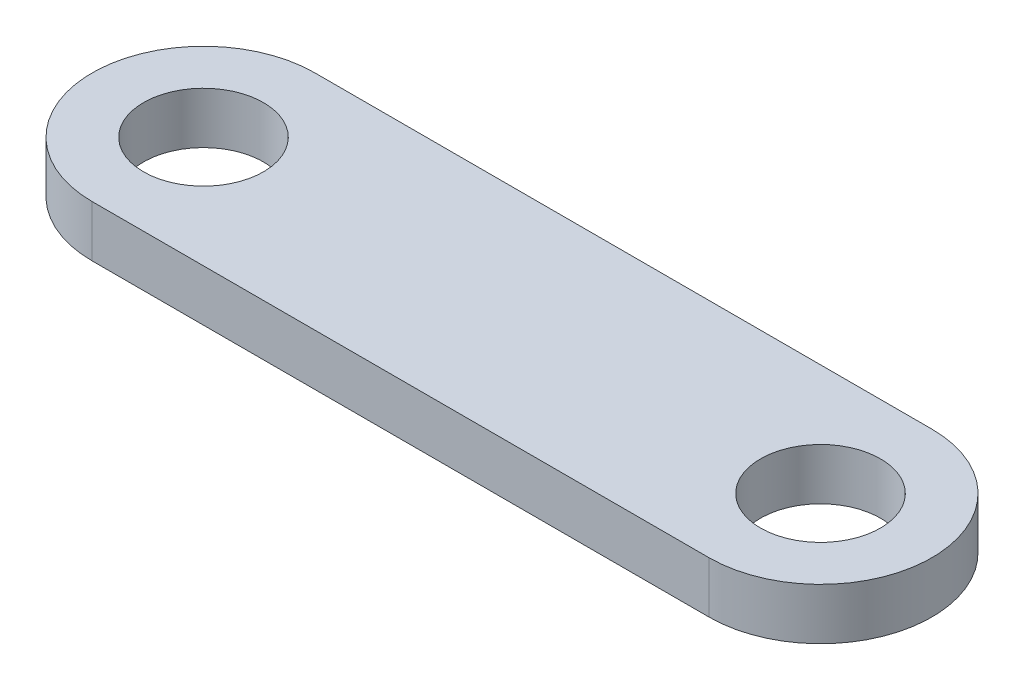
SolidWorks part; units mm, degrees
ref_plane "Front Plane" through (0, 0, 0) normal (0, 0, 1) x (1, 0, 0)
ref_plane "Top Plane" through (0, 0, 0) normal (0, 1, 0) x (1, 0, 0)
ref_plane "Right Plane" through (0, 0, 0) normal (1, 0, 0) x (0, 0, -1)
sketch "Sketch1" plane through (0, 0, 0) normal (0, 1, 0) x (1, 0, 0)
  line L0 (-18, 0) -> (18, 0) construction
  line L1 (-18, 0) -> (18, 0) construction
  line L2 (-18, 6.5) -> (18, 6.5)
  line L3 (-18, -6.5) -> (18, -6.5)
  arc A0 (-18, 6.5) -> (-18, -6.5) centre (-18, 0) ccw
  arc A1 (18, -6.5) -> (18, 6.5) centre (18, 0) ccw
  circle A2 centre (-18, 0) radius 3.5
  circle A3 centre (18, 0) radius 3.5
  point P3 (0, 0)
  point P4 (0, 0)
  dimension "D2" = 3
  dimension "D3" = 7
  dimension "D1" = 36
extrude "Boss-Extrude1" add sketch "Sketch1" along normal blind 3
